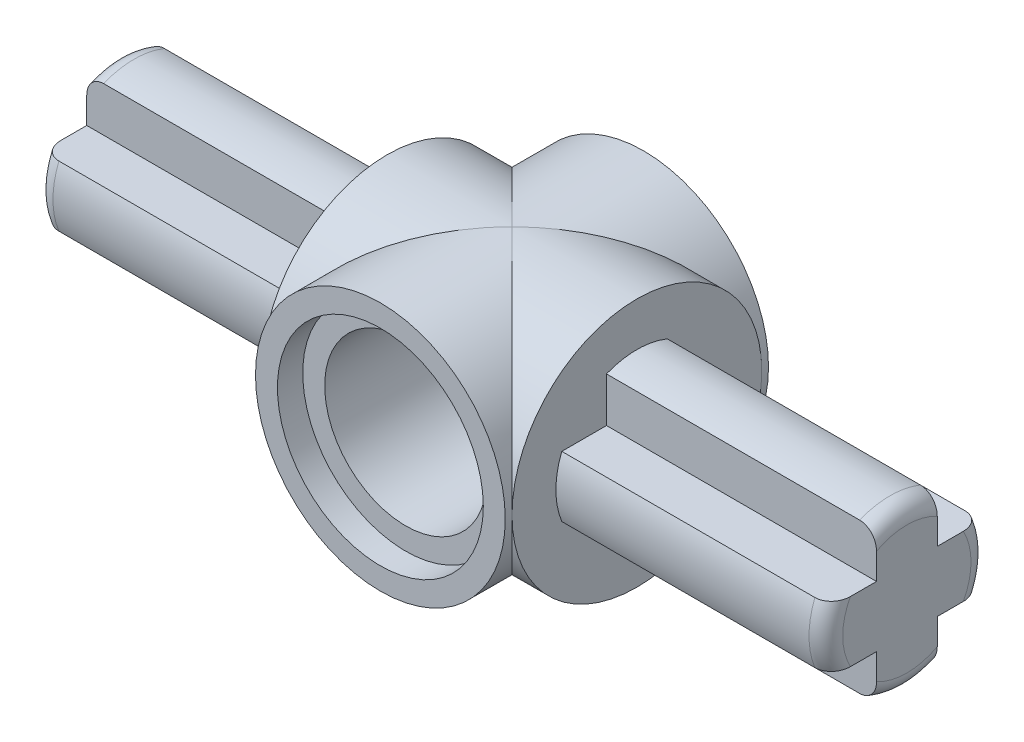
SolidWorks part; units mm, degrees
ref_plane "Front Plane" through (0, 0, 0) normal (0, 0, 1) x (1, 0, 0)
ref_plane "Top Plane" through (0, 0, 0) normal (0, 1, 0) x (1, 0, 0)
ref_plane "Right Plane" through (0, 0, 0) normal (1, 0, 0) x (0, 0, -1)
sketch "Sketch1" plane through (0, 0, 0) normal (1, 0, 0) x (0, 0, -1)
  line L1 (0.9, -2.4) -> (-0.9, -2.4)
  line L2 (0.9, -2.4) -> (0.9, 2.4)
  line L3 (0.9, 2.4) -> (-0.9, 2.4)
  line L4 (-0.9, -2.4) -> (-0.9, 2.4)
  line L5 (0.9, -2.4) -> (-0.9, 2.4) construction
  line L6 (0.9, 2.4) -> (-0.9, -2.4) construction
  line L7 (-2.4, -0.9) -> (2.4, -0.9)
  line L8 (-2.4, -0.9) -> (-2.4, 0.9)
  line L9 (-2.4, 0.9) -> (2.4, 0.9)
  line L10 (2.4, -0.9) -> (2.4, 0.9)
  line L11 (-2.4, -0.9) -> (2.4, 0.9) construction
  line L12 (-2.4, 0.9) -> (2.4, -0.9) construction
  circle A0 centre (0, 0) radius 2.4
  dimension "D1" = 4.8
  dimension "D2" = 1.8
extrude "Pin" add sketch "Sketch1" along normal mid plane 23.4 contours L2 A0 L4 L9 | L9 L4 L7 L2 | L9 A0 L7 L4 | L4 A0 L2 L7 | A0 L9 L2 L7
sketch "Sketch2" plane through (0, 0, 0) normal (1, 0, 0) x (0, 0, -1)
  circle A0 centre (0, 0) radius 3.7
  dimension "D1" = 7.4
extrude "Middle " add sketch "Sketch2" along normal mid plane 7.4
sketch "Sketch6" plane through (0, 0, 0) normal (0, 0, 1) x (1, 0, 0)
  circle A0 centre (0, 0) radius 3.7
  dimension "D1" = 7.4
extrude "Middle Body" add sketch "Sketch6" along normal mid plane 7.8
sketch "Sketch7" plane through (0, 0, 0) normal (0, 0, 1) x (1, 0, 0)
  circle A0 centre (0, 0) radius 2.4
  dimension "D1" = 4.8
extrude "Middle Bore " cut sketch "Sketch7" against normal through all both and the other way through all
sketch "Sketch8" plane through (0, 0, 3.9) normal (0, 0, 1) x (1, 0, 0)
  circle A0 centre (0, 0) radius 3.05
  dimension "D1" = 6.1
extrude "Middle Rim Cut " cut sketch "Sketch8" against normal blind 0.75
mirror "Mirror2" about plane through (0, 0, 0) normal (0, 0, 1) of "Middle Rim Cut "
fillet "Fillet1" radius 0.5 8 edges at (-11.7, -2.4, 0) (-11.7, 2.4, 0) (-11.7, 0, -2.4) (-11.7, 0, 2.4) (11.7, 0, 2.4) (11.7, 0, -2.4) (11.7, 2.4, 0) (11.7, -2.4, 0)
